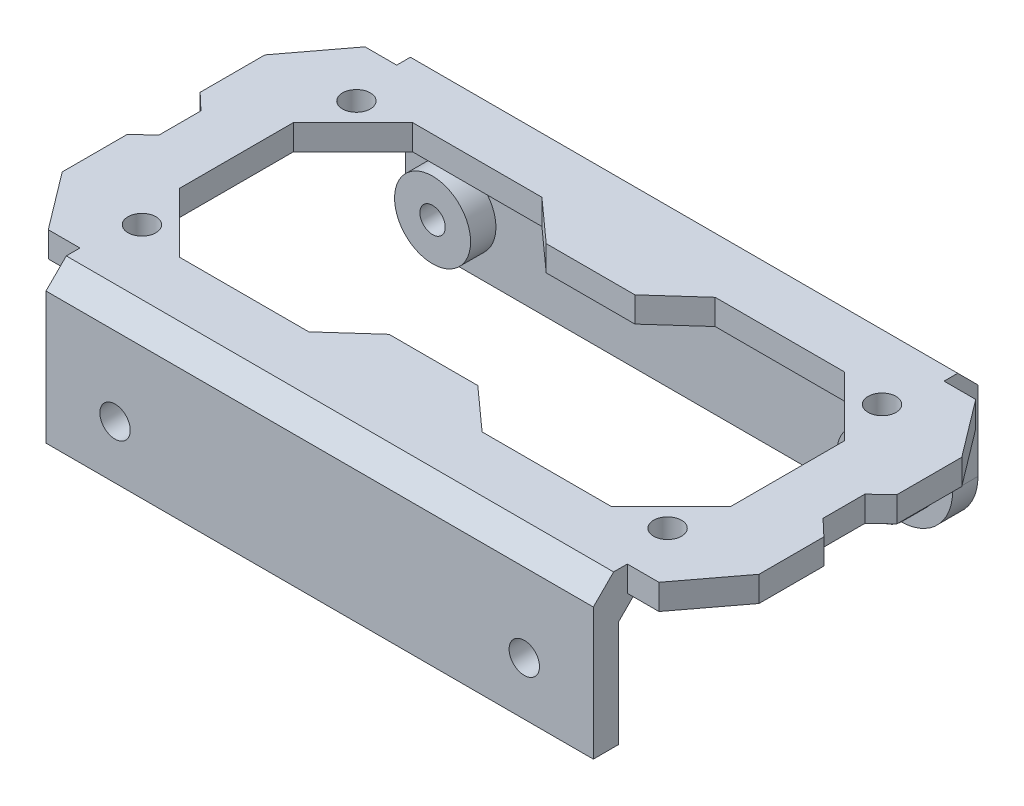
SolidWorks part; units mm, degrees
ref_plane "前视基准面" through (0, 0, 0) normal (0, 0, 1) x (1, 0, 0)
ref_plane "上视基准面" through (0, 0, 0) normal (0, 1, 0) x (1, 0, 0)
ref_plane "右视基准面" through (0, 0, 0) normal (1, 0, 0) x (0, 0, -1)
other "Configuration Table"
sketch "草图1" plane through (0, 0, 0) normal (0, 1, 0) x (1, 0, 0)
  line L0 (27.5, -8) -> (27.5, 8)
  line L1 (-27.5, -12.5) -> (27.5, -12.5)
  line L2 (-27.5, -12.5) -> (-27.5, 12.5)
  line L3 (-27.5, 12.5) -> (27.5, 12.5)
  line L4 (27.5, -12.5) -> (27.5, 12.5)
  line L5 (-27.5, -12.5) -> (27.5, 12.5) construction
  line L6 (-27.5, 12.5) -> (27.5, -12.5) construction
  line L7 (-21.6, 12.5) -> (21.6, 12.5)
  line L8 (27.5, 8) -> (24.5, 8)
  line L9 (-21.6, 12.5) -> (21.6, 12.5)
  line L10 (-21.6, 12.5) -> (-21.6, 15.18)
  line L11 (-21.6, 15.18) -> (21.6, 15.18)
  line L12 (21.6, 12.5) -> (21.6, 15.18)
  line L13 (21.6, 12.5) -> (24.1, 12.5)
  line L14 (24.1, 12.5) -> (27.5, 8)
  line L15 (27.5, -2.885) -> (27.5, 2.885)
  line L16 (27.5, -1.65) -> (27.5, 1.65)
  line L17 (27.5, -2.885) -> (26.2, -1.65)
  line L18 (27.5, 2.885) -> (26.2, 2.885)
  line L19 (27.5, 2.885) -> (27.5, -2.885)
  line L20 (27.5, -2.885) -> (26.2, -2.885)
  line L21 (26.2, 2.885) -> (26.2, -2.885)
  line L22 (27.5, 2.885) -> (26.2, 1.65)
  line L23 (21.75, -4.5) -> (21.75, 4.5)
  line L24 (4.9695, 0) -> (0, 0) construction
  line L25 (0, 0) -> (0, 3.4467) construction
  line L26 (-21.75, -9.2) -> (21.75, -9.2)
  line L27 (-21.75, -9.2) -> (-21.75, 9.2)
  line L28 (-21.75, 9.2) -> (21.75, 9.2)
  line L29 (21.75, -9.2) -> (21.75, 9.2)
  line L30 (-21.75, -9.2) -> (21.75, 9.2) construction
  line L31 (-21.75, 9.2) -> (21.75, -9.2) construction
  line L32 (21.75, 4.5) -> (17.05, 9.2)
  line L33 (-6.84, 9.2) -> (6.84, 9.2)
  line L34 (-3.5, 9.2) -> (3.5, 9.2)
  line L35 (-6.84, 9.2) -> (-3.5, 6.2)
  line L36 (-6.84, 9.2) -> (6.84, 9.2)
  line L37 (-6.84, 9.2) -> (-6.84, 6.2)
  line L38 (-6.84, 6.2) -> (6.84, 6.2)
  line L39 (6.84, 9.2) -> (6.84, 6.2)
  line L40 (-3.5, 9.2) -> (3.5, 9.2)
  line L41 (-3.5, 9.2) -> (-3.5, 6.2)
  line L42 (-3.5, 6.2) -> (3.5, 6.2)
  line L43 (3.5, 9.2) -> (3.5, 6.2)
  line L44 (6.84, 9.2) -> (3.5, 6.2)
  line L45 (24.1, -12.5) -> (27.5, -8)
  line L46 (-6.84, -9.2) -> (-3.5, -6.2)
  line L47 (6.84, -9.2) -> (3.5, -6.2)
  line L48 (21.75, -4.5) -> (17.05, -9.2)
  line L49 (-3.5, -6.2) -> (3.5, -6.2)
  line L50 (-21.75, -4.5) -> (-17.05, -9.2)
  line L51 (-21.75, 4.5) -> (-17.05, 9.2)
  line L52 (-24.1, 12.5) -> (-27.5, 8)
  line L53 (-24.1, -12.5) -> (-27.5, -8)
  line L54 (-27.5, -2.885) -> (-26.2, -1.65)
  line L55 (-27.5, 2.885) -> (-26.2, 1.65)
  line L56 (-26.2, 1.65) -> (-26.2, -1.65)
  line L57 (-21.6, -15.18) -> (21.6, -15.18)
  line L58 (21.6, -12.5) -> (21.6, -15.18)
  line L59 (-21.6, -12.5) -> (21.6, -12.5)
  line L60 (-21.6, -12.5) -> (-21.6, -15.18)
  point P0 (0, 0)
  point P9 (27.5, 0)
  point P12 (0, 12.5)
  point P19 (27.5, 0)
  point P22 (27.5, 0)
  point P34 (21.75, 0)
  point P38 (0, 9.2)
  point P41 (0, 9.2)
  dimension "D1" = 55
  dimension "D2" = 25
  dimension "D3" = 16
  dimension "D4" = 43.2
  dimension "D5" = 2.68
  dimension "D6" = 3
  dimension "D7" = 2.5
  dimension "D8" = 5.77
  dimension "D9" = 3.3
  dimension "D10" = 1.3
  dimension "D11" = 43.5
  dimension "D12" = 18.4
  dimension "D13" = 9
  dimension "D14" = 4.7
  dimension "D15" = 13.68
  dimension "D16" = 7
  dimension "D17" = 3
extrude "凸台-拉伸1" add sketch "草图1" along normal blind 2
sketch "草图2" plane through (0, 2, 0) normal (0, 1, 0) x (1, 0, 0)
  line L0 (21.75, 4.5) -> (17.05, 9.2) construction
  line L1 (21.75, 4.5) -> (17.05, 9.2)
  line L2 (24.1, 12.5) -> (19.4, 6.85)
  line L3 (19.4, 6.85) -> (20.0395, 7.6188)
  line L4 (17.05, 9.2) -> (21.75, 9.2)
  line L5 (17.05, 9.2) -> (17.05, 4.5)
  line L6 (17.05, 4.5) -> (21.75, 4.5)
  line L7 (21.75, 9.2) -> (21.75, 4.5)
  line L8 (19.643, 8.4644) -> (-19.643, 8.4644)
  line L9 (0, 0) -> (2.3478, 0)
  line L10 (0, 0) -> (0, 1.978)
  line L11 (0, 1.978) -> (2.3478, 1.978)
  line L12 (2.3478, 0) -> (2.3478, 1.978)
  line L13 (20.743, 7.3644) -> (20.743, -7.3644)
  line L24 (26.2, -1.65) -> (26.2, 1.65)
  line L25 (26.2, 1.65) -> (27.5, 2.885)
  line L26 (27.5, 2.885) -> (27.5, 8)
  line L27 (27.5, 8) -> (24.1, 12.5)
  line L28 (24.1, 12.5) -> (21.6, 12.5)
  line L29 (21.6, 12.5) -> (21.6, 15.18)
  line L30 (21.6, 15.18) -> (-21.6, 15.18)
  line L31 (-21.6, 15.18) -> (-21.6, 12.5)
  line L32 (-21.6, 12.5) -> (-24.1, 12.5)
  line L33 (-24.1, 12.5) -> (-27.5, 8)
  line L34 (-27.5, 8) -> (-27.5, 2.885)
  line L35 (-27.5, 2.885) -> (-26.2, 1.65)
  line L36 (-26.2, 1.65) -> (-26.2, -1.65)
  line L37 (-26.2, -1.65) -> (-27.5, -2.885)
  line L38 (-27.5, -2.885) -> (-27.5, -8)
  line L39 (-27.5, -8) -> (-24.1, -12.5)
  line L40 (-24.1, -12.5) -> (-21.6, -12.5)
  line L41 (-21.6, -12.5) -> (-21.6, -15.18)
  line L42 (-21.6, -15.18) -> (21.6, -15.18)
  line L43 (21.6, -15.18) -> (21.6, -12.5)
  line L44 (21.6, -12.5) -> (24.1, -12.5)
  line L45 (24.1, -12.5) -> (27.5, -8)
  line L46 (27.5, -8) -> (27.5, -2.885)
  line L47 (27.5, -2.885) -> (26.2, -1.65)
  line L48 (26.2, -1.65) -> (26.2, 1.65)
  line L49 (26.2, 1.65) -> (27.5, 2.885)
  line L50 (27.5, 2.885) -> (27.5, 8)
  line L51 (27.5, 8) -> (24.1, 12.5)
  line L52 (24.1, 12.5) -> (21.6, 12.5)
  line L53 (21.6, 12.5) -> (21.6, 15.18)
  line L54 (21.6, 15.18) -> (-21.6, 15.18)
  line L55 (-21.6, 15.18) -> (-21.6, 12.5)
  line L56 (-21.6, 12.5) -> (-24.1, 12.5)
  line L57 (-24.1, 12.5) -> (-27.5, 8)
  line L58 (-27.5, 8) -> (-27.5, 2.885)
  line L59 (-27.5, 2.885) -> (-26.2, 1.65)
  line L60 (-26.2, 1.65) -> (-26.2, -1.65)
  line L61 (-26.2, -1.65) -> (-27.5, -2.885)
  line L62 (-27.5, -2.885) -> (-27.5, -8)
  line L63 (-27.5, -8) -> (-24.1, -12.5)
  line L64 (-24.1, -12.5) -> (-21.6, -12.5)
  line L65 (-21.6, -12.5) -> (-21.6, -15.18)
  line L66 (-21.6, -15.18) -> (21.6, -15.18)
  line L67 (21.6, -15.18) -> (21.6, -12.5)
  line L68 (21.6, -12.5) -> (24.1, -12.5)
  line L69 (24.1, -12.5) -> (27.5, -8)
  line L70 (27.5, -8) -> (27.5, -2.885)
  line L71 (27.5, -2.885) -> (26.2, -1.65)
  circle A0 centre (20.743, 8.4644) radius 1.1
  circle A1 centre (20.743, -8.4644) radius 1.1
  circle A2 centre (-20.743, -8.4644) radius 1.1
  circle A3 centre (-20.743, 8.4644) radius 1.1
  dimension "D2" = 1
  dimension "D3" = 1.1
  dimension "D1" = 0
extrude "切除-拉伸1" cut sketch "草图2" against normal blind 2 contours A3 | A2 | A1 | L2 A0 L4 | L2 A0 | L4 A0
sketch "草图3" plane through (0, 0, 0) normal (0, -1, 0) x (1, 0, 0)
  line L1 (-21.6, 15.18) -> (21.6, 15.18)
  line L2 (-21.6, 15.18) -> (-21.6, 13.18)
  line L3 (-21.6, 13.18) -> (21.6, 13.18)
  line L4 (21.6, 15.18) -> (21.6, 13.18)
  line L5 (21.6, -15.18) -> (-21.6, -15.18)
  line L6 (21.6, -15.18) -> (21.6, -13.18)
  line L7 (21.6, -13.18) -> (-21.6, -13.18)
  line L8 (-21.6, -15.18) -> (-21.6, -13.18)
  line L24 (26.2, -1.65) -> (26.2, 1.65)
  line L25 (26.2, 1.65) -> (27.5, 2.885)
  line L26 (27.5, 2.885) -> (27.5, 8)
  line L27 (27.5, 8) -> (24.1, 12.5)
  line L28 (24.1, 12.5) -> (21.6, 12.5)
  line L29 (21.6, 12.5) -> (21.6, 15.18)
  line L30 (21.6, 15.18) -> (-21.6, 15.18)
  line L31 (-21.6, 15.18) -> (-21.6, 12.5)
  line L32 (-21.6, 12.5) -> (-24.1, 12.5)
  line L33 (-24.1, 12.5) -> (-27.5, 8)
  line L34 (-27.5, 8) -> (-27.5, 2.885)
  line L35 (-27.5, 2.885) -> (-26.2, 1.65)
  line L36 (-26.2, 1.65) -> (-26.2, -1.65)
  line L37 (-26.2, -1.65) -> (-27.5, -2.885)
  line L38 (-27.5, -2.885) -> (-27.5, -8)
  line L39 (-27.5, -8) -> (-24.1, -12.5)
  line L40 (-24.1, -12.5) -> (-21.6, -12.5)
  line L41 (-21.6, -12.5) -> (-21.6, -15.18)
  line L42 (-21.6, -15.18) -> (21.6, -15.18)
  line L43 (21.6, -15.18) -> (21.6, -12.5)
  line L44 (21.6, -12.5) -> (24.1, -12.5)
  line L45 (24.1, -12.5) -> (27.5, -8)
  line L46 (27.5, -8) -> (27.5, -2.885)
  line L47 (27.5, -2.885) -> (26.2, -1.65)
  line L48 (26.2, -1.65) -> (26.2, 1.65)
  line L49 (26.2, 1.65) -> (27.5, 2.885)
  line L50 (27.5, 2.885) -> (27.5, 8)
  line L51 (27.5, 8) -> (24.1, 12.5)
  line L52 (24.1, 12.5) -> (21.6, 12.5)
  line L53 (21.6, 12.5) -> (21.6, 15.18)
  line L54 (21.6, 15.18) -> (-21.6, 15.18)
  line L55 (-21.6, 15.18) -> (-21.6, 12.5)
  line L56 (-21.6, 12.5) -> (-24.1, 12.5)
  line L57 (-24.1, 12.5) -> (-27.5, 8)
  line L58 (-27.5, 8) -> (-27.5, 2.885)
  line L59 (-27.5, 2.885) -> (-26.2, 1.65)
  line L60 (-26.2, 1.65) -> (-26.2, -1.65)
  line L61 (-26.2, -1.65) -> (-27.5, -2.885)
  line L62 (-27.5, -2.885) -> (-27.5, -8)
  line L63 (-27.5, -8) -> (-24.1, -12.5)
  line L64 (-24.1, -12.5) -> (-21.6, -12.5)
  line L65 (-21.6, -12.5) -> (-21.6, -15.18)
  line L66 (-21.6, -15.18) -> (21.6, -15.18)
  line L67 (21.6, -15.18) -> (21.6, -12.5)
  line L68 (21.6, -12.5) -> (24.1, -12.5)
  line L69 (24.1, -12.5) -> (27.5, -8)
  line L70 (27.5, -8) -> (27.5, -2.885)
  line L71 (27.5, -2.885) -> (26.2, -1.65)
  line M48 (21.6, 12.5) -> (21.6, 15.18)
  line M49 (21.6, 15.18) -> (-21.6, 15.18)
  line M50 (-21.6, 15.18) -> (-21.6, 12.5)
  line M60 (-21.6, -12.5) -> (-21.6, -15.18)
  line M61 (-21.6, -15.18) -> (21.6, -15.18)
  line M62 (21.6, -15.18) -> (21.6, -12.5)
  dimension "D2" = 2
  dimension "D3" = 2
  dimension "D1" = 0
extrude "凸台-拉伸2" add sketch "草图3" along normal blind 10 contours L7 M62 M60 M61 | L3 M50 M48 M49
sketch "草图4" plane through (0, 0, -15.18) normal (0, 0, -1) x (-1, 0, 0)
  line L0 (18.45, -5.85) -> (21.6, -5.85)
  line L1 (17.45, -6.85) -> (17.45, -10)
  line L2 (0, -10) -> (0, -5.85)
  line L4 (-21.6, 2) -> (-21.6, -10)
  line L5 (-21.6, -10) -> (21.6, -10)
  line L6 (21.6, -10) -> (21.6, 2)
  line L7 (21.6, 2) -> (-21.6, 2)
  line L8 (-21.6, 2) -> (-21.6, -10)
  line L9 (-21.6, -10) -> (21.6, -10)
  line L10 (21.6, -10) -> (21.6, 2)
  line L11 (21.6, 2) -> (-21.6, 2)
  circle A0 centre (17.45, -5.85) radius 1
  circle A1 centre (-17.45, -5.85) radius 1
  circle A2 centre (-17.45, -5.85) radius 4.15
  circle A3 centre (17.45, -5.85) radius 4.15
  line M11 (-21.6, -10) -> (21.6, -10)
  line M12 (21.6, -10) -> (21.6, 2)
  dimension "D2" = 2
  dimension "D3" = 3.15
  dimension "D4" = 3.15
  dimension "D1" = 0
extrude "切除-拉伸2" cut sketch "草图4" against normal up to surface (2 mm away) contours A1 | A2 L8 M11 | A0 | A3 M11 M12 up to face at (0, -5, -13.18)
sketch "草图5" plane through (0, 0, -13.18) normal (0, 0, 1) x (1, 0, 0)
  line L4 (21.6, -5.85) -> (21.6, 0)
  line L5 (21.6, 0) -> (-21.6, 0)
  line L6 (-21.6, 0) -> (-21.6, -5.85)
  line L7 (-17.45, -10) -> (17.45, -10)
  line L8 (21.6, -5.85) -> (21.6, 0)
  line L9 (21.6, 0) -> (-21.6, 0)
  line L10 (-21.6, 0) -> (-21.6, -5.85)
  line L11 (-17.45, -10) -> (17.45, -10)
  circle A0 centre (-17.45, -5.85) radius 1 construction
  circle A1 centre (-17.45, -5.85) radius 1
  arc A2 (17.45, -10) -> (21.6, -5.85) centre (17.45, -5.85) ccw
  arc A3 (-21.6, -5.85) -> (-17.45, -10) centre (-17.45, -5.85) ccw
  arc A4 (17.45, -10) -> (21.6, -5.85) centre (17.45, -5.85) ccw
  arc A5 (-21.6, -5.85) -> (-17.45, -10) centre (-17.45, -5.85) ccw
  circle A6 centre (17.45, -5.85) radius 1 construction
  circle A7 centre (17.45, -5.85) radius 1
  circle A8 centre (-17.45, -5.85) radius 3
  circle A9 centre (17.45, -5.85) radius 3
  circle M15 centre (17.45, -5.85) radius 1
  circle M16 centre (-17.45, -5.85) radius 1
  dimension "D1" = 0
  dimension "D2" = 2
extrude "凸台-拉伸3" add sketch "草图5" along normal blind 2 contours A9 M15 | A8 M16
chamfer "倒角2" distance 1.6 angle 45 4 edges at (0, 2, 15.18) (0, 0, 13.18) (0, 0, -13.18) (0, 2, -15.18)
sketch "草图7" plane through (21.6, 0, 0) normal (1, 0, 0) x (0, 0, -1)
  line L0 (11.58, 0) -> (12.5, 0)
  line L1 (-11.58, 0) -> (-12.5, 0)
  line L5 (8, 0) -> (11.58, 0)
  line L6 (11.58, 0) -> (12.5, -0.92)
  line L7 (15.18, -5.85) -> (15.18, 0.4)
  line L8 (15.18, 0.4) -> (13.58, 2)
  line L9 (13.58, 2) -> (12.5, 2)
  line L10 (12.5, 2) -> (12.5, -0.92)
  line L11 (12.5, -0.92) -> (13.18, -1.6)
  line L12 (13.18, -1.6) -> (13.18, -5.85)
  line L13 (13.18, -5.85) -> (15.18, -5.85)
  line L14 (15.18, -5.85) -> (15.18, 0.4)
  line L15 (15.18, 0.4) -> (13.58, 2)
  line L16 (13.58, 2) -> (12.5, 2)
  line L17 (12.5, 2) -> (12.5, -0.92)
  line L18 (12.5, -0.92) -> (13.18, -1.6)
  line L19 (13.18, -1.6) -> (13.18, -5.85)
  line L20 (13.18, -5.85) -> (15.18, -5.85)
  line L21 (12.5, -0.92) -> (12.5, 2)
  line L22 (12.5, 2) -> (8, 2)
  line L23 (8, 2) -> (8, 0)
  line L24 (8, 0) -> (11.58, 0)
  line L25 (11.58, 0) -> (12.5, -0.92)
  line L26 (12.5, -0.92) -> (12.5, 2)
  line L27 (12.5, 2) -> (8, 2)
  line L28 (8, 2) -> (8, 0)
  line L30 (-12.5, 2) -> (-12.5, -0.92)
  line L31 (-12.5, -0.92) -> (-11.58, 0)
  line L32 (-11.58, 0) -> (-8, 0)
  line L33 (-8, 0) -> (-8, 2)
  line L34 (-8, 2) -> (-12.5, 2)
  line L35 (-12.5, 2) -> (-12.5, -0.92)
  line L36 (-12.5, -0.92) -> (-11.58, 0)
  line L37 (-11.58, 0) -> (-8, 0)
  line L38 (-8, 0) -> (-8, 2)
  line L39 (-8, 2) -> (-12.5, 2)
  line L42 (-12.5, 2) -> (-13.58, 2)
  line L43 (-13.58, 2) -> (-15.18, 0.4)
  line L44 (-15.18, 0.4) -> (-15.18, -10)
  line L45 (-15.18, -10) -> (-13.18, -10)
  line L46 (-13.18, -10) -> (-13.18, -1.6)
  line L47 (-13.18, -1.6) -> (-12.5, -0.92)
  line L48 (-12.5, -0.92) -> (-12.5, 2)
  line L49 (-12.5, 2) -> (-13.58, 2)
  line L50 (-13.58, 2) -> (-15.18, 0.4)
  line L51 (-15.18, 0.4) -> (-15.18, -10)
  line L53 (-13.18, -10) -> (-13.18, -1.6)
  line L54 (-13.18, -1.6) -> (-12.5, -0.92)
  line L55 (-12.5, -0.92) -> (-12.5, 2)
  line L57 (-15.18, -10) -> (-13.18, -10)
  line M28 (12.5, 2) -> (12.5, -0.92)
  dimension "D1" = 0
  dimension "D2" = 0
  dimension "D3" = 0
  dimension "D4" = 0
extrude "切除-拉伸3" cut sketch "草图7" along normal up to surface (5.9 mm away) contours L35 L36 L1 | L0 L25 M28 up to face at (27.5, 1, 5.4425)
sketch "草图8" plane through (-27.5, 0, 0) normal (-1, 0, 0) x (0, 0, 1)
  line L0 (-11.58, 0) -> (-12.5, 0)
  line L1 (11.58, 0) -> (12.5, 0)
  line L4 (2.885, 0) -> (8, 0)
  line L5 (8, 0) -> (8, 2)
  line L6 (8, 2) -> (2.885, 2)
  line L7 (2.885, 2) -> (2.885, 0)
  line L8 (2.885, 0) -> (8, 0)
  line L9 (8, 0) -> (8, 2)
  line L10 (8, 2) -> (2.885, 2)
  line L11 (2.885, 2) -> (2.885, 0)
  line L13 (8, 0) -> (11.58, 0)
  line L14 (11.58, 0) -> (12.5, -0.92)
  line L15 (12.5, -0.92) -> (12.5, 2)
  line L16 (12.5, 2) -> (8, 2)
  line L17 (8, 2) -> (8, 0)
  line L18 (8, 0) -> (11.58, 0)
  line L19 (11.58, 0) -> (12.5, -0.92)
  line L20 (12.5, -0.92) -> (12.5, 2)
  line L21 (12.5, 2) -> (8, 2)
  line L22 (8, 2) -> (8, 0)
  line L23 (-12.5, 2) -> (-12.5, -0.92)
  line L24 (-12.5, -0.92) -> (-11.58, 0)
  line L25 (15.18, -10) -> (15.18, 0.4)
  line L26 (15.18, 0.4) -> (13.58, 2)
  line L27 (13.58, 2) -> (12.5, 2)
  line L28 (12.5, 2) -> (12.5, -0.92)
  line L29 (12.5, -0.92) -> (13.18, -1.6)
  line L30 (13.18, -1.6) -> (13.18, -10)
  line L31 (13.18, -10) -> (15.18, -10)
  line L32 (15.18, -10) -> (15.18, 0.4)
  line L33 (15.18, 0.4) -> (13.58, 2)
  line L34 (13.58, 2) -> (12.5, 2)
  line L35 (12.5, 2) -> (12.5, -0.92)
  line L36 (12.5, -0.92) -> (13.18, -1.6)
  line L37 (13.18, -1.6) -> (13.18, -10)
  line L39 (-11.58, 0) -> (-8, 0)
  line L40 (-8, 0) -> (-8, 2)
  line L41 (-8, 2) -> (-12.5, 2)
  line L42 (-12.5, 2) -> (-12.5, -0.92)
  line L43 (-12.5, -0.92) -> (-11.58, 0)
  line L44 (-11.58, 0) -> (-8, 0)
  line L45 (-8, 0) -> (-8, 2)
  line L46 (-8, 2) -> (-12.5, 2)
  line L51 (13.18, -10) -> (15.18, -10)
  dimension "D1" = 0
  dimension "D2" = 0
  dimension "D3" = 0
  dimension "D4" = 0
extrude "切除-拉伸4" cut sketch "草图8" against normal up to surface (5.9 mm away) contours L19 L20 L1 | L42 L43 L0 up to face at (-21.6, -1.4029, -13.6143)
sketch "草图9" plane through (0, 0, 15.18) normal (0, 0, 1) x (1, 0, 0)
  line L0 (-14.95, -5.8) -> (14.95, -5.8)
  line L1 (-17.35, -5.8) -> (-21.6, -5.8)
  line L2 (17.35, -5.8) -> (21.6, -5.8)
  line L3 (-16.15, -7) -> (-16.15, -10)
  line L4 (21.6, -10) -> (21.6, 0.4)
  line L5 (21.6, 0.4) -> (-21.6, 0.4)
  line L6 (-21.6, 0.4) -> (-21.6, -10)
  line L7 (-21.6, -10) -> (21.6, -10)
  line L8 (21.6, -10) -> (21.6, 0.4)
  line L9 (21.6, 0.4) -> (-21.6, 0.4)
  line L10 (-21.6, 0.4) -> (-21.6, -10)
  line L11 (-21.6, -10) -> (21.6, -10)
  circle A0 centre (-16.15, -5.8) radius 1.2
  circle A1 centre (16.15, -5.8) radius 1.2
  dimension "D3" = 2.4
  dimension "D4" = 2.4
  dimension "D2" = 29.9
  dimension "D5" = 3
  dimension "D1" = 0
extrude "切除-拉伸5" cut sketch "草图9" against normal blind 10 contours A0 | A1 L8
sketch "草图11" plane through (0, 2, 0) normal (0, 1, 0) x (1, 0, 0)
  line L24 (-21.6, -12.5) -> (-21.6, -13.58)
  line L25 (-21.6, -13.58) -> (21.6, -13.58)
  line L26 (21.6, -13.58) -> (21.6, -12.5)
  line L27 (21.6, -12.5) -> (24.1, -12.5)
  line L28 (24.1, -12.5) -> (27.5, -8)
  line L29 (27.5, -8) -> (27.5, -2.885)
  line L30 (27.5, -2.885) -> (26.2, -1.65)
  line L31 (26.2, -1.65) -> (26.2, 1.65)
  line L32 (26.2, 1.65) -> (27.5, 2.885)
  line L33 (27.5, 2.885) -> (27.5, 8)
  line L34 (27.5, 8) -> (24.1, 12.5)
  line L35 (24.1, 12.5) -> (21.6, 12.5)
  line L36 (21.6, 12.5) -> (21.6, 13.58)
  line L37 (21.6, 13.58) -> (-21.6, 13.58)
  line L38 (-21.6, 13.58) -> (-21.6, 12.5)
  line L39 (-21.6, 12.5) -> (-24.1, 12.5)
  line L40 (-24.1, 12.5) -> (-27.5, 8)
  line L41 (-27.5, 8) -> (-27.5, 2.885)
  line L42 (-27.5, 2.885) -> (-26.2, 1.65)
  line L43 (-26.2, 1.65) -> (-26.2, -1.65)
  line L44 (-26.2, -1.65) -> (-27.5, -2.885)
  line L45 (-27.5, -2.885) -> (-27.5, -8)
  line L46 (-27.5, -8) -> (-24.1, -12.5)
  line L47 (-24.1, -12.5) -> (-21.6, -12.5)
  line L48 (-21.6, -12.5) -> (-21.6, -13.58)
  line L49 (-21.6, -13.58) -> (21.6, -13.58)
  line L50 (21.6, -13.58) -> (21.6, -12.5)
  line L51 (21.6, -12.5) -> (24.1, -12.5)
  line L52 (24.1, -12.5) -> (27.5, -8)
  line L53 (27.5, -8) -> (27.5, -2.885)
  line L54 (27.5, -2.885) -> (26.2, -1.65)
  line L55 (26.2, -1.65) -> (26.2, 1.65)
  line L56 (26.2, 1.65) -> (27.5, 2.885)
  line L57 (27.5, 2.885) -> (27.5, 8)
  line L58 (27.5, 8) -> (24.1, 12.5)
  line L59 (24.1, 12.5) -> (21.6, 12.5)
  line L60 (21.6, 12.5) -> (21.6, 13.58)
  line L61 (21.6, 13.58) -> (-21.6, 13.58)
  line L62 (-21.6, 13.58) -> (-21.6, 12.5)
  line L63 (-21.6, 12.5) -> (-24.1, 12.5)
  line L64 (-24.1, 12.5) -> (-27.5, 8)
  line L65 (-27.5, 8) -> (-27.5, 2.885)
  line L66 (-27.5, 2.885) -> (-26.2, 1.65)
  line L67 (-26.2, 1.65) -> (-26.2, -1.65)
  line L68 (-26.2, -1.65) -> (-27.5, -2.885)
  line L69 (-27.5, -2.885) -> (-27.5, -8)
  line L70 (-27.5, -8) -> (-24.1, -12.5)
  line L71 (-24.1, -12.5) -> (-21.6, -12.5)
  arc A0 (21.4464, 9.3101) -> (21.75, 8.0218) centre (20.743, 8.4644) ccw construction
  arc A1 (21.4464, 9.3101) -> (21.75, 8.0218) centre (20.743, 8.4644) ccw
  circle A2 centre (20.743, 8.4644) radius 1.1
  line M25 (21.4464, 9.3101) -> (21.3549, 9.2)
  line M26 (21.3549, 9.2) -> (21.5609, 9.2)
  arc M27 (21.5609, 9.2) -> (21.75, 8.9071) centre (20.743, 8.4644) cw
  line M28 (21.75, 8.9071) -> (21.75, 8.0218)
  arc M29 (21.75, 8.0218) -> (21.4464, 9.3101) centre (20.743, 8.4644) cw
  dimension "D1" = 0
extrude "切除-拉伸7" cut sketch "草图11" against normal blind 10 contours M25 M29 M28 M27 M26 | A2 M28 | A2 M26 M25
